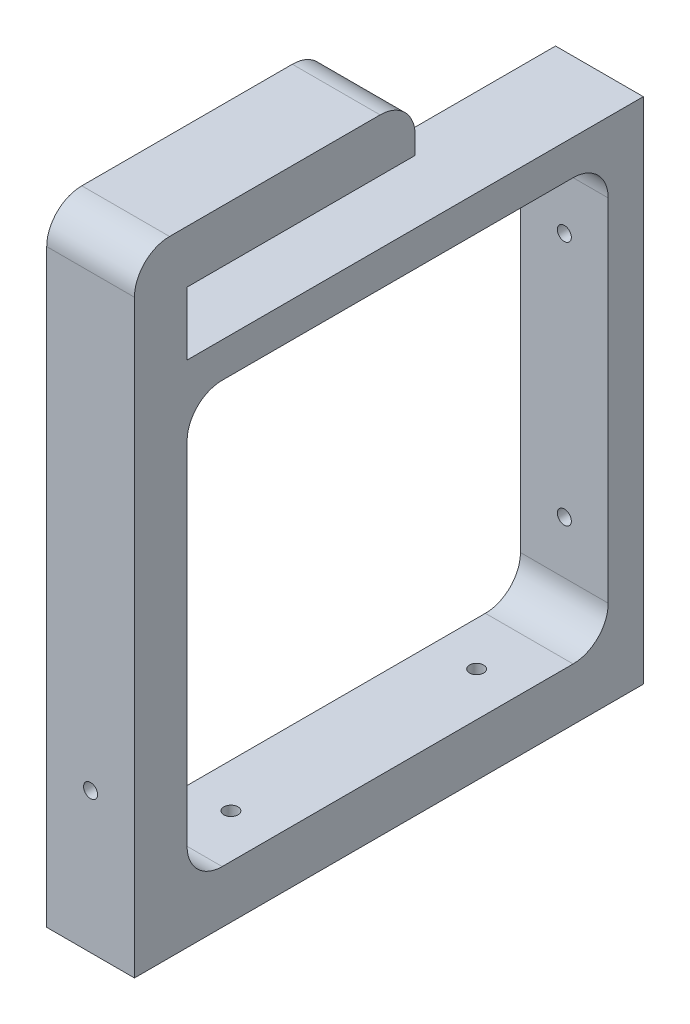
SolidWorks part; units mm, degrees
ref_plane "Plan de face" through (0, 0, 0) normal (0, 0, 1) x (1, 0, 0)
ref_plane "Plan de dessus" through (0, 0, 0) normal (0, 1, 0) x (1, 0, 0)
ref_plane "Plan de droite" through (0, 0, 0) normal (1, 0, 0) x (0, 0, -1)
sketch "Esquisse1" plane through (0, 0, 0) normal (1, 0, 0) x (0, 0, -1)
  line L0 (0, 0) -> (145, 0)
  line L1 (145, 0) -> (145, 145)
  line L2 (145, 145) -> (15, 145)
  line L3 (15, 145) -> (15, 163)
  line L4 (15, 163) -> (80, 163)
  line L5 (80, 163) -> (80, 178)
  line L6 (80, 178) -> (0, 178)
  line L7 (0, 178) -> (0, 0)
  line L8 (15, 135) -> (15, 15)
  line L9 (15, 15) -> (135, 15)
  line L10 (135, 15) -> (135, 135)
  line L11 (135, 135) -> (15, 135)
  dimension "D1" = 15
  dimension "D2" = 15
  dimension "D3" = 15
  dimension "D4" = 120
  dimension "D5" = 10
  dimension "D6" = 120
  dimension "D7" = 10
  dimension "D8" = 18
  dimension "D9" = 15
  dimension "D10" = 80
extrude "Boss.-Extru.1" add sketch "Esquisse1" along normal blind 25
sketch "Esquisse2" plane through (0, 15, 0) normal (0, 1, 0) x (1, 0, 0)
  line L2 (12.5, 27.1506) -> (12.5, 96.9425) construction
  line L3 (25, 15) -> (25, 135) construction
  line L4 (0, 15) -> (0, 135) construction
  line L5 (25, 15) -> (0, 15) construction
  line L6 (25, 135) -> (0, 135) construction
  circle A0 centre (12.5, 40) radius 2
  circle A1 centre (12.5, 110) radius 2
  point P10 (0, 0)
  point P11 (0, 0)
  dimension "D3" = 4
  dimension "D4" = 4
  dimension "D1" = 25
  dimension "D2" = 25
extrude "Enlèv. mat.-Extru.1" cut sketch "Esquisse2" against normal through all
sketch "Esquisse3" plane through (0, 0, -135) normal (0, 0, 1) x (1, 0, 0)
  line L0 (12.5, 90.0233) -> (12.5, 53.6926) construction
  line L1 (25, 15) -> (25, 135) construction
  line L2 (0, 15) -> (0, 135) construction
  line L3 (25, 15) -> (0, 15) construction
  line L4 (25, 135) -> (0, 135) construction
  circle A0 centre (12.5, 40) radius 2
  circle A1 centre (12.5, 110) radius 2
  point P10 (0, 0)
  point P11 (0, 0)
  dimension "D2" = 4
  dimension "D4" = 4
  dimension "D1" = 25
  dimension "D3" = 25
extrude "Enlèv. mat.-Extru.2" cut sketch "Esquisse3" against normal through all
sketch "Esquisse4" plane through (0, 0, -15) normal (0, 0, -1) x (-1, 0, 0)
  line L0 (-12.5, 101.625) -> (-12.5, 95.3633) construction
  line L1 (-25, 135) -> (-25, 15) construction
  line L2 (0, 135) -> (0, 15) construction
  line L3 (-25, 15) -> (0, 15) construction
  circle A0 centre (-12.5, 40) radius 2
  point P8 (0, 0)
  point P9 (0, 0)
  dimension "D2" = 4
  dimension "D1" = 25
extrude "Enlèv. mat.-Extru.3" cut sketch "Esquisse4" against normal through all
fillet "Congé1" radius 10 2 edges at (12.5, 178, 0) (12.5, 178, -80)
fillet "Congé2" radius 10 4 edges at (12.5, 15, -135) (12.5, 135, -135) (12.5, 135, -15) (12.5, 15, -15)
